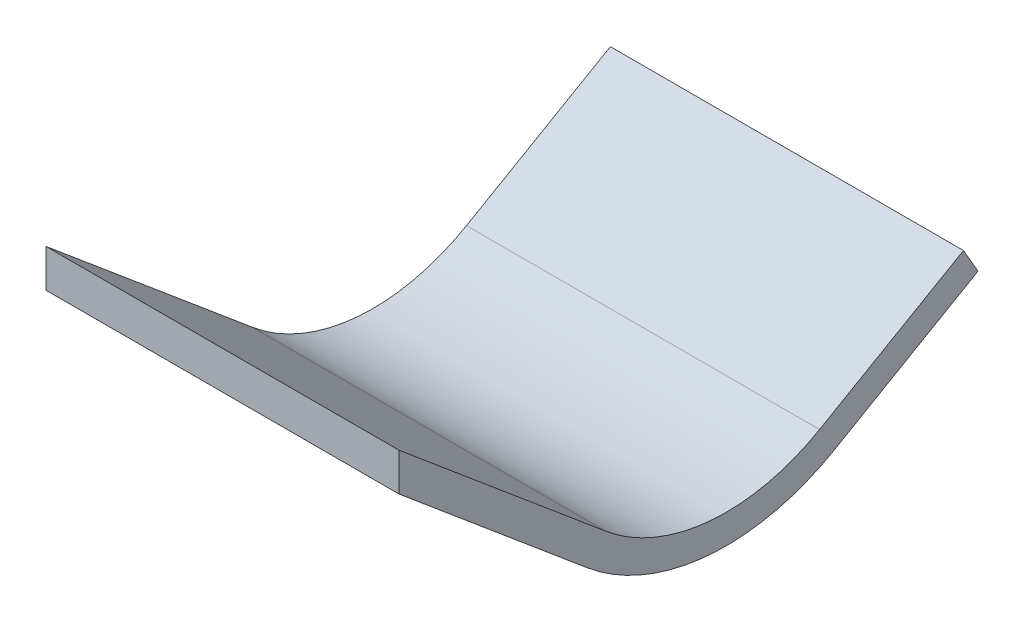
SolidWorks part; units mm, degrees
ref_plane "Front Plane" through (0, 0, 0) normal (0, 0, 1) x (1, 0, 0)
ref_plane "Top Plane" through (0, 0, 0) normal (0, 1, 0) x (1, 0, 0)
ref_plane "Right Plane" through (0, 0, 0) normal (1, 0, 0) x (0, 0, -1)
sketch "Sketch1" plane through (0, 0, 0) normal (1, 0, 0) x (0, 0, -1)
  line L0 (-72.0409, 10.2395) -> (-22.2485, -31.5423)
  line L1 (29.1769, -36.0421) -> (63.8181, -16.0426)
  line L2 (-72.0409, 1.1015) -> (-26.7481, -36.9046)
  line L3 (32.6768, -42.1044) -> (67.3181, -22.1048)
  line L5 (63.8181, -16.0426) -> (67.3181, -22.1048)
  line L6 (-72.0409, 10.2395) -> (-72.0409, 1.1015)
  line L7 (-76.5405, 4.8772) -> (-26.7481, -36.9046) construction
  arc A0 (-22.2485, -31.5423) -> (29.1769, -36.0421) centre (6.6774, 2.9293) ccw
  arc A1 (-26.7481, -36.9046) -> (32.6768, -42.1044) centre (6.6774, 2.9293) ccw
  point P10 (2.1446, -48.8728)
  dimension "D1" = 7
  dimension "D5" = 45
  dimension "D2" = 65
  dimension "D3" = 40
  dimension "D6" = 110
extrude "Boss-Extrude1" add sketch "Sketch1" along normal blind 85
